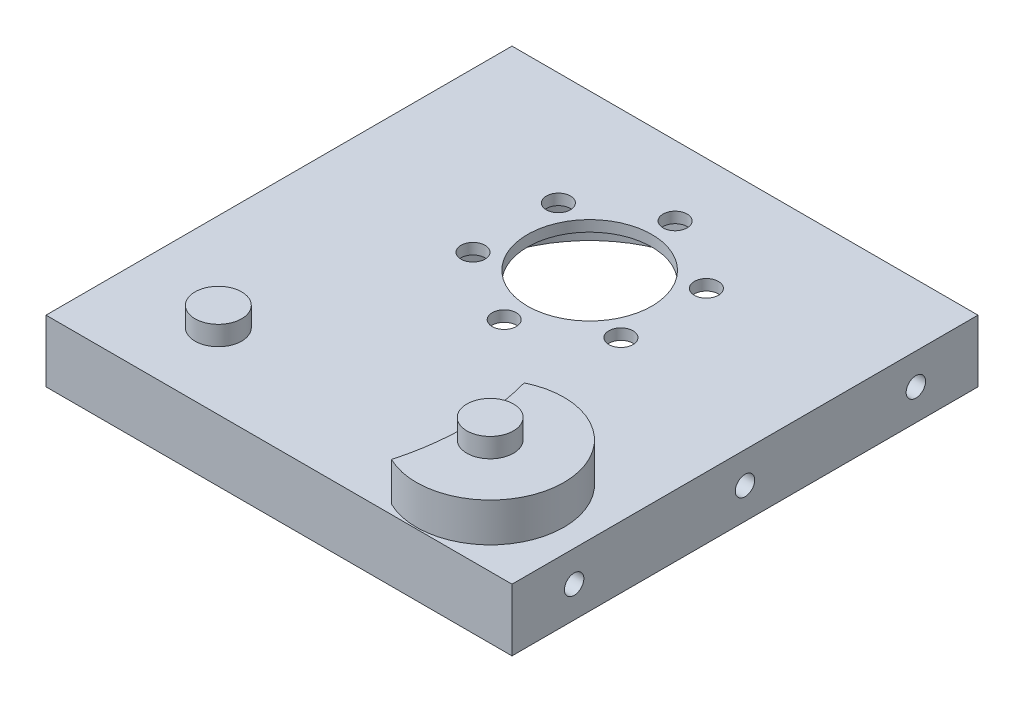
SolidWorks part; units mm, degrees
material "5052-O"
ref_plane "Plan de face" through (0, 0, 0) normal (0, 0, 1) x (1, 0, 0)
ref_plane "Plan de dessus" through (0, 0, 0) normal (0, 1, 0) x (1, 0, 0)
ref_plane "Plan de droite" through (0, 0, 0) normal (1, 0, 0) x (0, 0, -1)
sketch "Sketch1" plane through (0, 0, 0) normal (0, 1, 0) x (1, 0, 0)
  line L0 (0, 0) -> (0, 10) construction
  line L1 (-30, 30) -> (30, 30)
  line L2 (-30, 30) -> (-30, -30)
  line L3 (-30, -30) -> (30, -30)
  line L4 (30, 30) -> (30, -30)
  line L5 (-30, 30) -> (30, -30) construction
  line L6 (-30, -30) -> (30, 30) construction
  circle A0 centre (0, 10) radius 16
  point P0 (0, 0)
  dimension "D1" = 32
  dimension "D2" = 60
  dimension "D3" = 60
  dimension "D4" = 10
extrude "Boss-Extrude1" add sketch "Sketch1" along normal blind 8
sketch "Sketch2" plane through (0, 8, 0) normal (0, 1, 0) x (1, 0, 0)
  line L0 (0, 10) -> (-17.5, -20.3109) construction
  line L1 (-17.5, -20.3109) -> (17.5, -20.3109) construction
  line L3 (-30, -30) -> (30, -30) construction
  line L4 (0, 10) -> (0, -20.3109) construction
  circle A0 centre (-17.5, -20.3109) radius 3
  circle A1 centre (17.5, -20.3109) radius 3
  circle A2 centre (17.5, -20.3109) radius 3
  dimension "D3" = 6
  dimension "D4" = 6
  dimension "D1" = 35
  dimension "D2" = 35
extrude "Boss-Extrude2" add sketch "Sketch2" along normal blind 2.5 contours A0 | A1
sketch "Sketch3" plane through (0, 8, 0) normal (0, 1, 0) x (1, 0, 0)
  line L0 (30, 30) -> (-30, 30) construction
  line L1 (-0.5, 25.9922) -> (0.5, 25.9922)
  line L2 (-0.5, 25.9922) -> (-0.5, 30)
  line L3 (-0.5, 30) -> (0.5, 30)
  line L4 (0.5, 25.9922) -> (0.5, 30)
  line L5 (-0.5, 25.9922) -> (0.5, 30) construction
  line L6 (-0.5, 30) -> (0.5, 25.9922) construction
  line L7 (-3.5, 30) -> (-3.5, 28.6748)
  line L8 (-19, 10) -> (-30, 10)
  line L9 (-30, 30) -> (-30, -30) construction
  line L10 (-30, 10) -> (-30, 30)
  line L11 (-30, 30) -> (-3.5, 30)
  line L12 (0, 10) -> (0, 16.5756) construction
  line L13 (30, 30) -> (3.5, 30)
  line L14 (30, 10) -> (30, 30)
  line L15 (19, 10) -> (30, 10)
  line L16 (3.5, 30) -> (3.5, 28.6748)
  circle A0 centre (0, 10) radius 16 construction
  arc A2 (-3.5, 28.6748) -> (-19, 10) centre (0, 10) ccw
  arc A3 (3.5, 28.6748) -> (19, 10) centre (0, 10) cw
  point P0 (0, 27.9961)
  dimension "D3" = 3
  dimension "D1" = 1
  dimension "D2" = 3
extrude "Cut-Extrude1" [suppressed] cut sketch "Sketch3" against normal through all
hole_wizard "Ø2.0mm Dowel Hole1" [suppressed] positions "Sketch4" profile "Sketch5" hole size "Ø2.0" standard "ISO"
sketch "Sketch4" [suppressed] plane through (3.5, 0, 0) normal (1, 0, 0) x (0, 0, -1)
  line L0 (32.5, 0) -> (32.5, 5) construction
  line L2 (32.5, 5) -> (26.1748, 5) construction
  point P0 (29.5, 2.5)
  point P2 (29.5, 2.5)
  dimension "D1" = 3
  dimension "D2" = 2.5
sketch "Sketch5" plane through (3.5, 2.5, -29.5) normal (0, 1, 0) x (0, 0, -1)
  line L0 (0, 0) -> (0, 33.5)
  line L1 (0, 33.5) -> (1, 33.5)
  line L2 (1, 33.5) -> (1, 0)
  line L5 (1, 0) -> (0, 0)
  line L11 (0, -6.35) -> (0, 107.95) construction
  dimension "Thru Hole Dia." = 2
  dimension "Thru Hole Depth" = 33.5
sketch "Sketch7" plane through (0, 10.5, 0) normal (0, 1, 0) x (1, 0, 0)
  circle A0 centre (17.5, -20.3109) radius 3
extrude "Boss-Extrude3" add sketch "Sketch7" along normal blind 5
sketch "Sketch8" plane through (0, 8, 0) normal (0, 1, 0) x (1, 0, 0)
  arc A0 (13.3393, -28.8513) -> (13.3393, -11.7705) centre (17.5, -20.3109) ccw
  arc A1 (13.3393, -28.8513) -> (13.3393, -11.7705) centre (-17.5, -20.3109) ccw
  dimension "D1" = 19
  dimension "D2" = 32
extrude "Boss-Extrude4" add sketch "Sketch8" along normal blind 5
sketch "Sketch9" plane through (0, 8, 0) normal (0, 1, 0) x (1, 0, 0)
  circle A0 centre (0, 10) radius 8
  circle A1 centre (0, 10) radius 16 construction
  circle A2 centre (0, 10) radius 16
  dimension "D1" = 8
extrude "Boss-Extrude5" add sketch "Sketch9" against normal blind 1.4
sketch "Sketch10" plane through (0, 8, 0) normal (0, 1, 0) x (1, 0, 0)
  line L0 (0, 10) -> (0, 21) construction
  circle A0 centre (0, 21) radius 1.55
  dimension "D2" = 3.1
  dimension "D1" = 11
extrude "Cut-Extrude2" cut sketch "Sketch10" against normal through all
pattern_circular "CirPattern1" count 6 over 360 about axis through (0, 0, -10) along (0, 1, 0) of "Cut-Extrude2"
hole_wizard "M3 Tapped Hole2" positions "Sketch15" profile "Sketch16" tap size "M3" standard "ISO"
sketch "Sketch15" plane through (30, 0, 0) normal (1, 0, 0) x (0, 0, -1)
  line L0 (-30, 0) -> (30, 0) construction
  point P0 (-22, 4)
  point P2 (0, 4)
  point P4 (22, 4)
  point P12 (0, 0)
  point P14 (0, 0)
  dimension "D1" = 22
  dimension "D2" = 22
  dimension "D3" = 4
sketch "Sketch16" plane through (30, 4, 22) normal (0, 1, 0) x (0, 0, -1)
  line L0 (0, 0) -> (0, 8.2511)
  line L1 (0, 8.2511) -> (1.25, 7.5)
  line L2 (1.25, 7.5) -> (1.25, 0)
  line L5 (1.25, 0) -> (0, 0)
  line L10 (0, 8.2511) -> (-1.25, 7.5) construction
  line L11 (0, -6.35) -> (0, 107.95) construction
  dimension "Tap Drill Dia." = 2.5
  dimension "Tap Drill Depth" = 7.5
  dimension "Drill Angle" = 118
cosmetic thread "Hole Thread4" parameters "D1"=6, "D2"=3
cosmetic thread "Hole Thread5" parameters "D1"=6, "D2"=3
cosmetic thread "Hole Thread6" parameters "D1"=6, "D2"=3
mirror "Mirror1" about plane through (0, 0, 0) normal (1, 0, 0) of "M3 Tapped Hole2"
cosmetic thread "Hole Thread7" parameters "D1"=6, "D2"=3
cosmetic thread "Hole Thread8" parameters "D1"=6, "D2"=3
cosmetic thread "Hole Thread9" parameters "D1"=6, "D2"=3
